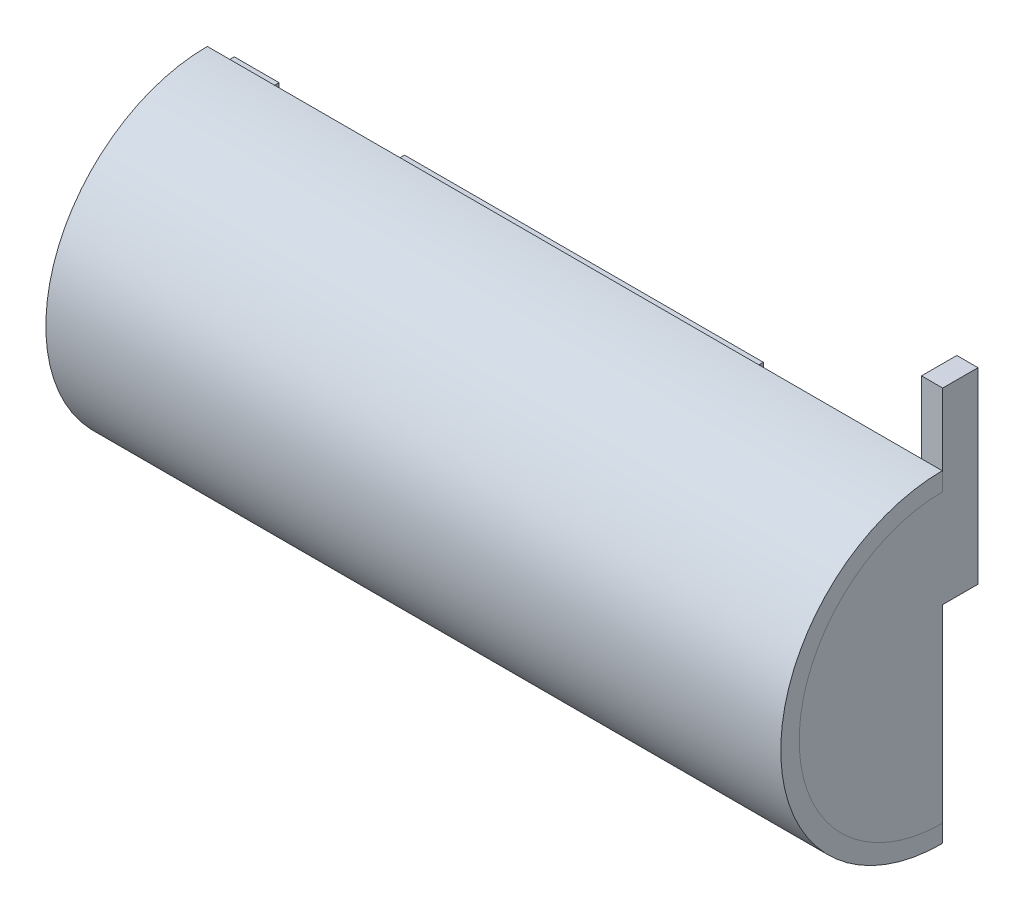
SolidWorks part; units mm, degrees
ref_plane "Front Plane" through (0, 0, 0) normal (0, 0, 1) x (1, 0, 0)
ref_plane "Top Plane" through (0, 0, 0) normal (0, 1, 0) x (1, 0, 0)
ref_plane "Right Plane" through (0, 0, 0) normal (1, 0, 0) x (0, 0, -1)
sketch "Sketch2" plane through (0, 0, 0) normal (0, 0, 1) x (1, 0, 0)
  line L0 (0, 0) -> (0, 40.64)
  line L1 (0, 0) -> (5.08, 0)
  line L2 (5.08, 0) -> (5.08, 40.64)
  line L3 (0, 40.64) -> (0, 45.72)
  line L4 (0, 45.72) -> (25.4, 45.72)
  line L6 (5.08, 40.64) -> (25.4, 40.64)
  line L8 (208.1, 45.72) -> (195.4, 45.72)
  line L9 (195.4, 45.72) -> (25.4, 45.72)
  line L10 (208.2277, 40.64) -> (195.5277, 40.64)
  line L11 (195.5277, 40.64) -> (25.4, 40.64)
  line L12 (208.1, 45.72) -> (208.2277, 40.64)
  dimension "D8" = 5.08
  dimension "D1" = 40.64
  dimension "D2" = 5.08
  dimension "D3" = 40.64
  dimension "D4" = 5.08
  dimension "D5" = 25.4
  dimension "D6" = 170
  dimension "D7" = 12.7
  dimension "D9" = 180
  dimension "D10" = 12.7
revolve "Revolve2" add sketch "Sketch2" angle 180 about L1
sketch "Sketch5" plane through (0, 0, 0) normal (0, 0, -1) x (-1, 0, 0)
  line L0 (-5.08, 40.64) -> (0, 40.64) construction
  line L1 (-3.81, 40.64) -> (-1.27, 40.64)
  line L2 (-3.81, 40.64) -> (-3.81, 27.94)
  line L3 (-3.81, 27.94) -> (-1.27, 27.94)
  line L4 (-1.27, 40.64) -> (-1.27, 27.94)
  line L5 (0, -45.72) -> (0, 45.72) construction
  line L6 (-5.08, 40.64) -> (-5.08, 45.72) construction
  line L7 (-208.1, 45.72) -> (0, 45.72) construction
  line L8 (-154.9139, -41.91) -> (-154.9139, -44.45)
  line L9 (-5.08, 44.45) -> (-17.78, 44.45)
  line L10 (-5.08, 44.45) -> (-5.08, 41.91)
  line L11 (-5.08, 41.91) -> (-17.78, 41.91)
  line L12 (-17.78, 44.45) -> (-17.78, 41.91)
  line L13 (-154.9139, -44.45) -> (-53.3139, -44.45)
  line L14 (-53.3139, -44.45) -> (-53.3139, -41.91)
  line L15 (-53.3139, -41.91) -> (-154.9139, -41.91)
  line L16 (-312.3416, -45.72) -> (104.1139, -45.72) construction
  line L17 (-53.3139, -41.91) -> (-53.3139, -45.72) construction
  line L18 (-53.3139, -44.45) -> (-53.3139, -40.64) construction
  line L19 (104.1139, -40.64) -> (-312.3416, -40.64) construction
  line L20 (-154.9139, -40.64) -> (-154.9139, -44.45) construction
  line L21 (-154.9139, -41.91) -> (-154.9139, -45.72) construction
  line L22 (0, 0) -> (-208.2277, 0) construction
  line L23 (-208.2277, -40.64) -> (-208.2277, 40.64) construction
  line L24 (-53.3139, 44.45) -> (-53.3139, 41.91)
  line L25 (-154.9139, 44.45) -> (-53.3139, 44.45)
  line L26 (-154.9139, 41.91) -> (-154.9139, 44.45)
  line L27 (-53.3139, 41.91) -> (-154.9139, 41.91)
  line L28 (-5.08, -41.91) -> (-17.78, -41.91)
  line L29 (-17.78, -44.45) -> (-17.78, -41.91)
  line L30 (-5.08, -44.45) -> (-17.78, -44.45)
  line L31 (-5.08, -44.45) -> (-5.08, -41.91)
  line L32 (-3.81, -27.94) -> (-1.27, -27.94)
  line L33 (-1.27, -40.64) -> (-1.27, -27.94)
  line L34 (-3.81, -40.64) -> (-1.27, -40.64)
  line L35 (-3.81, -40.64) -> (-3.81, -27.94)
  point P9 (-2.54, 40.64)
  point P10 (-2.54, 40.64)
  point P18 (-5.08, 43.18)
  point P19 (-5.08, 43.18)
  point P26 (-104.1139, -45.72)
  point P27 (-104.1139, -41.91)
  dimension "D1" = 12.7
  dimension "D2" = 2.54
  dimension "D3" = 12.7
  dimension "D4" = 2.54
  dimension "D5" = 2.54
  dimension "D6" = 2.54
  dimension "D7" = 101.6
extrude "Boss-Extrude1" add sketch "Sketch5" along normal blind 2.54 contours L15 L8 L13 L14 | L10 L9 L12 L11 | L2 L1 L4 L3 | L32 L33 L34 L35 | L28 L29 L30 L31 | L24 L27 L26 L25
sketch "Sketch7" plane through (0, 0, 0) normal (-1, 0, 0) x (0, 0, 1)
  line L0 (0, 25) -> (0, -25)
  line L1 (0, 25) -> (20, 25)
  line L2 (0, -25) -> (20, -25)
  line L3 (20, 25) -> (20, -25)
  line L4 (0, -45.72) -> (0, 45.72) construction
  point P6 (0, 0)
  dimension "D1" = 50
  dimension "D2" = 20
extrude "Cut-Extrude1" cut sketch "Sketch7" against normal blind 7
sketch "Sketch8" plane through (0, 0, 0) normal (0, 0, -1) x (-1, 0, 0)
  line L0 (-208.1, 45.72) -> (0, 45.72) construction
  line L1 (-13.08, 45.72) -> (-18.08, 45.72)
  line L2 (-13.08, 45.72) -> (-13.08, -45.72)
  line L3 (-13.08, -45.72) -> (-18.08, -45.72)
  line L4 (-18.08, 45.72) -> (-18.08, -45.72)
  line L5 (-5.08, 40.64) -> (-5.08, 25) construction
  line L8 (-208.1, -45.72) -> (0, -45.72) construction
  dimension "D1" = 5
  dimension "D3" = 8
extrude "Boss-Extrude3" add sketch "Sketch8" against normal up to next
sketch "Sketch9" plane through (5.08, 0, 0) normal (1, 0, 0) x (0, 0, -1)
  line L1 (-0.8418, 37.9918) -> (-6.9711, 37.9918)
  line L2 (-0.8418, 37.9918) -> (-0.8418, 29.9132)
  line L3 (-0.8418, 29.9132) -> (-6.9711, 29.9132)
  line L4 (-6.9711, 37.9918) -> (-6.9711, 29.9132)
extrude "Boss-Extrude4" add sketch "Sketch9" along normal blind 2
sketch "Sketch12" plane through (13.08, 0, 0) normal (-1, 0, 0) x (0, 0, 1)
  line L0 (23.64, 33.0569) -> (23.64, -33.0569)
  line L1 (20, -25) -> (20, 25) construction
  arc A0 (23.64, 33.0569) -> (23.64, -33.0569) centre (0, 0) cw
  arc A2 (0, -40.64) -> (0, 40.64) centre (0, 0) ccw construction
  point P3 (23.64, 0)
  point P5 (40.64, 0)
  dimension "D1" = 17
extrude "Boss-Extrude7" add sketch "Sketch12" along normal up to surface (8 mm away) up to face at (5.08, 0, 13.44)
sketch "Sketch13" plane through (0, 0, 0) normal (0, 0, -1) x (-1, 0, 0)
  line L0 (-18.08, -40.64) -> (-208.2277, -40.64) construction
  line L1 (-113.1539, 27.5) -> (-183.1539, 27.5)
  line L2 (-113.1539, 27.5) -> (-113.1539, -27.5)
  line L3 (-113.1539, -27.5) -> (-183.1539, -27.5)
  line L4 (-183.1539, 27.5) -> (-183.1539, -27.5)
  line L5 (-110.6139, 30.04) -> (-185.6939, 30.04)
  line L6 (-110.6139, 30.04) -> (-110.6139, -30.04)
  line L7 (-110.6139, -30.04) -> (-185.6939, -30.04)
  line L8 (-185.6939, 30.04) -> (-185.6939, -30.04)
  line L9 (-113.1539, 40.64) -> (-113.1539, -40.64) construction
  line L10 (-18.08, 40.64) -> (-208.2277, 40.64) construction
  point P14 (-113.1539, 0)
  point P15 (-113.1539, 0)
  dimension "D1" = 55
  dimension "D2" = 70
  dimension "D3" = 2.54
  dimension "D4" = 2.54
  dimension "D5" = 2.54
  dimension "D6" = 2.54
extrude "Boss-Extrude8" add sketch "Sketch13" against normal up to surface (29.9226 mm away)
sketch "Sketch14" plane through (0, 0, 0) normal (0, 0, -1) x (-1, 0, 0)
  line L1 (-110.6139, 30.04) -> (-185.6939, 30.04)
  line L2 (-110.6139, 30.04) -> (-110.6139, -30.04)
  line L3 (-110.6139, -30.04) -> (-185.6939, -30.04)
  line L4 (-185.6939, 30.04) -> (-185.6939, -30.04)
extrude "Cut-Extrude3" cut sketch "Sketch14" against normal blind 11
sketch "Sketch15" plane through (0, 0, 11) normal (0, 0, -1) x (-1, 0, 0)
  line L1 (-113.1539, 27.5) -> (-183.1539, 27.5)
  line L2 (-113.1539, 27.5) -> (-113.1539, -27.5)
  line L3 (-113.1539, -27.5) -> (-183.1539, -27.5)
  line L4 (-183.1539, 27.5) -> (-183.1539, -27.5)
extrude "Boss-Extrude9" add sketch "Sketch15" against normal up to next
sketch "Sketch17" plane through (0, 0, 11) normal (0, 0, -1) x (-1, 0, 0)
  line L0 (-110.6139, 30.04) -> (-185.6939, 30.04) construction
  line L1 (-113.1539, 27.5) -> (-183.1539, 27.5)
  line L2 (-113.1539, 27.5) -> (-113.1539, -27.5)
  line L3 (-113.1539, -27.5) -> (-183.1539, -27.5)
  line L4 (-183.1539, 27.5) -> (-183.1539, 19.5)
  line L5 (-185.6939, 30.04) -> (-185.6939, -30.04) construction
  line L6 (-185.6939, -30.04) -> (-110.6139, -30.04) construction
  line L7 (-110.6139, -30.04) -> (-110.6139, 30.04) construction
  line L8 (-183.1539, 5.5) -> (-183.1539, -13.5)
  line L9 (-183.1539, 19.5) -> (-185.6939, 19.5)
  line L11 (-183.1539, 5.5) -> (-185.6939, 5.5)
  line L12 (-185.6939, 19.5) -> (-185.6939, 5.5)
  line L13 (-183.1539, -24.5) -> (-185.6939, -24.5)
  line L15 (-183.1539, -13.5) -> (-185.6939, -13.5)
  line L16 (-185.6939, -24.5) -> (-185.6939, -13.5)
  line L17 (-183.1539, -24.5) -> (-183.1539, -27.5)
  dimension "D1" = 2.54
  dimension "D2" = 2.54
  dimension "D3" = 2.54
  dimension "D4" = 2.54
  dimension "D5" = 8
  dimension "D6" = 22
  dimension "D7" = 14
  dimension "D8" = 3
extrude "Cut-Extrude5" cut sketch "Sketch17" against normal blind 15
sketch "Sketch18" plane through (18.08, 0, 0) normal (1, 0, 0) x (0, 0, -1)
  line L0 (0, 40.64) -> (0, -40.64) construction
  line L1 (0, 17.9952) -> (-12, 17.9952)
  line L2 (0, 17.9952) -> (0, -38.0048)
  line L3 (0, -38.0048) -> (-12, -38.0048)
  line L4 (-12, 17.9952) -> (-12, -38.0048)
  dimension "D1" = 12
  dimension "D2" = 56
  dimension "D3" = 2.6352
extrude "Cut-Extrude6" cut sketch "Sketch18" against normal up to next
sketch "Sketch23" plane through (0, 0, 0) normal (0, 0, -1) x (-1, 0, 0)
  line L0 (-18.08, -40.64) -> (-208.2277, -40.64) construction
  line L1 (-208.2277, 40.64) -> (-202.2277, 40.64)
  line L2 (-208.2277, 40.64) -> (-208.2277, -40.64)
  line L3 (-208.2277, -40.64) -> (-202.2277, -40.64)
  line L4 (-202.2277, 40.64) -> (-202.2277, -40.64)
  dimension "D1" = 6
extrude "Boss-Extrude10" add sketch "Sketch23" against normal up to surface up to face at (9.08, 37.7731, 12.1166)
sketch "Sketch26" plane through (0, 0, 0) normal (0, 0, -1) x (-1, 0, 0)
  line L0 (-202.2277, -40.64) -> (-202.2277, 40.64) construction
  line L1 (-202.2277, 66.0536) -> (-208.2277, 66.0536)
  line L2 (-202.2277, 66.0536) -> (-202.2277, 12.9464)
  line L3 (-202.2277, 12.9464) -> (-208.2277, 12.9464)
  line L4 (-208.2277, 66.0536) -> (-208.2277, 12.9464)
  line L5 (-208.2277, 40.64) -> (-208.2277, -40.64) construction
  point P9 (0, 0)
  point P12 (-208.2277, 39.5)
  point P13 (-208.2277, 0)
  dimension "D1" = 39.5
extrude "Boss-Extrude11" add sketch "Sketch26" along normal blind 10
